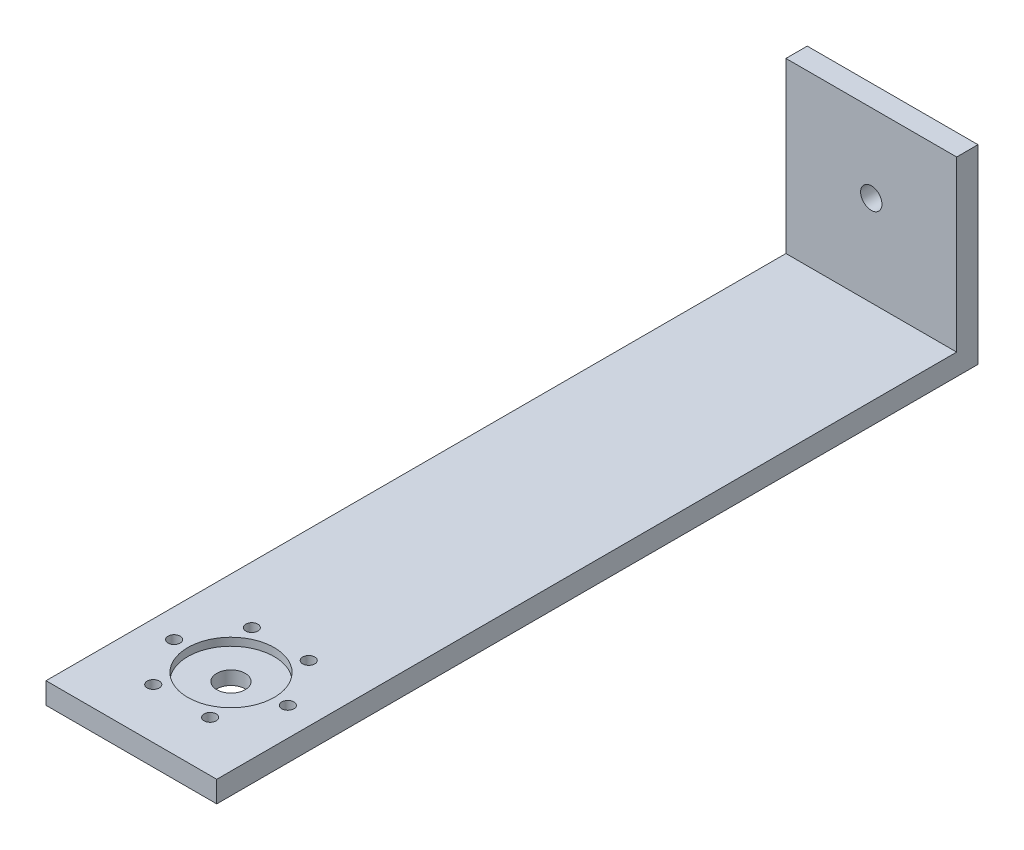
SolidWorks part; units mm, degrees
ref_plane "Front Plane" through (0, 0, 0) normal (0, 0, 1) x (1, 0, 0)
ref_plane "Top Plane" through (0, 0, 0) normal (0, 1, 0) x (1, 0, 0)
ref_plane "Right Plane" through (0, 0, 0) normal (1, 0, 0) x (0, 0, -1)
ref_plane "PL_Forearm_Plate_base" through (0, -31.5, 0) normal (0, 1, 0) x (1, 0, 0)
sketch "SK_Forearm_Plate" plane through (0, -31.5, 0) normal (0, 1, 0) x (1, 0, 0)
  line L0 (-24, -28) -> (24, -28)
  line L1 (24, -28) -> (24, 180)
  line L2 (24, 180) -> (-24, 180)
  line L3 (-24, 180) -> (-24, -28)
  circle A0 centre (16, 0) radius 1.7
  circle A1 centre (8, 13.8564) radius 1.7
  circle A2 centre (-8, 13.8564) radius 1.7
  circle A3 centre (-16, 0) radius 1.7
  circle A4 centre (-8, -13.8564) radius 1.7
  circle A5 centre (8, -13.8564) radius 1.7
  circle A6 centre (0, 0) radius 4
  dimension "D9_SK_Forearm_Plate" = 3.4
  dimension "D11_SK_Forearm_Plate" = 3.4
  dimension "D14_SK_Forearm_Plate" = 3.4
  dimension "D17_SK_Forearm_Plate" = 3.4
  dimension "D19_SK_Forearm_Plate" = 3.4
  dimension "D22_SK_Forearm_Plate" = 3.4
  dimension "D25_SK_Forearm_Plate" = 8
  dimension "P1" = 24
  dimension "P2" = 28
  dimension "P3" = 24
  dimension "P4" = 28
  dimension "P5" = 24
  dimension "P6" = 180
  dimension "P7" = 24
  dimension "P8" = 180
  dimension "P10" = 16
  dimension "P12" = 8
  dimension "P13" = 13.8564
  dimension "P15" = 8
  dimension "P16" = 13.8564
  dimension "P18" = 16
  dimension "P20" = 8
  dimension "P21" = 13.8564
  dimension "P23" = 8
  dimension "P24" = 13.8564
extrude "Forearm_Plate" add sketch "SK_Forearm_Plate" along normal blind 6
ref_plane "PL_Elbow_Pilot_Recess_base" through (0, -25.5, 0) normal (0, 1, 0) x (1, 0, 0)
sketch "SK_Elbow_Pilot_Recess" plane through (0, -25.5, 0) normal (0, 1, 0) x (1, 0, 0)
  circle A0 centre (0, 0) radius 12.15
  dimension "D1_SK_Elbow_Pilot_Recess" = 24.3
extrude "Elbow_Pilot_Recess" cut sketch "SK_Elbow_Pilot_Recess" against normal blind 2.2
ref_plane "PL_Hand_Plate_base" through (0, 0, -186) normal (0, 0, 1) x (1, 0, 0)
sketch "SK_Hand_Plate" plane through (0, 0, -186) normal (0, 0, 1) x (1, 0, 0)
  line L0 (-24, 22) -> (24, 22)
  line L1 (24, 22) -> (24, -31.5)
  line L2 (24, -31.5) -> (-24, -31.5)
  line L3 (-24, -31.5) -> (-24, 22)
  circle A0 centre (0, 0) radius 3
  dimension "D9_SK_Hand_Plate" = 6
  dimension "P1" = 24
  dimension "P2" = 22
  dimension "P3" = 24
  dimension "P4" = 22
  dimension "P5" = 24
  dimension "P6" = 31.5
  dimension "P7" = 24
  dimension "P8" = 31.5
extrude "Hand_Plate" add sketch "SK_Hand_Plate" along normal blind 6
equation "\"Forearm_length\" = 180"
